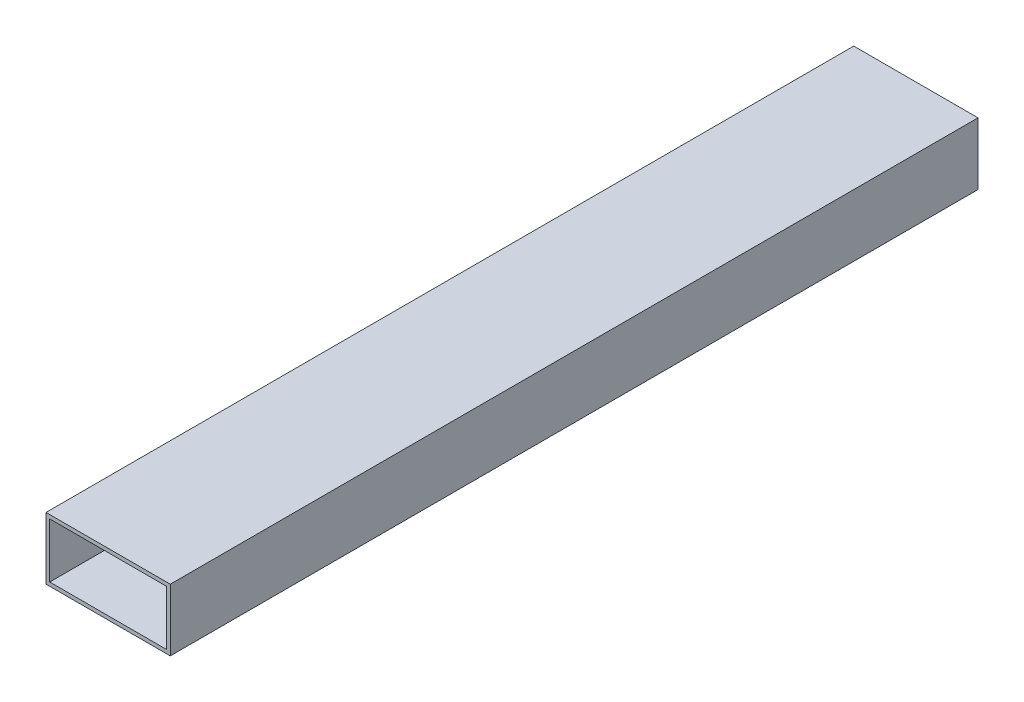
SolidWorks part; units mm, degrees
ref_plane "Front Plane" through (0, 0, 0) normal (0, 0, 1) x (1, 0, 0)
ref_plane "Top Plane" through (0, 0, 0) normal (0, 1, 0) x (1, 0, 0)
ref_plane "Right Plane" through (0, 0, 0) normal (1, 0, 0) x (0, 0, -1)
sketch "Sketch1" plane through (0, 0, 0) normal (0, 0, 1) x (1, 0, 0)
  line L1 (0, 0) -> (-50.8, 0)
  line L2 (0, 0) -> (0, 25.4)
  line L3 (0, 25.4) -> (-50.8, 25.4)
  line L4 (-50.8, 0) -> (-50.8, 25.4)
  dimension "D1" = 50.8
  dimension "D2" = 25.4
extrude "Extrude-Thin1" add sketch "Sketch1" along normal blind 330.2 thin
